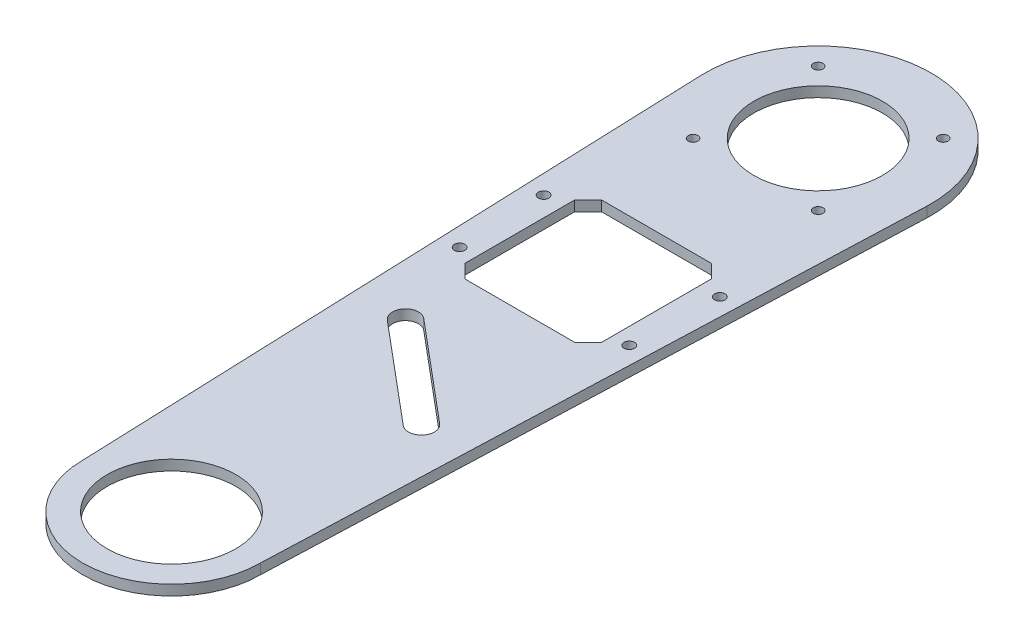
SolidWorks part; units mm, degrees
ref_plane "Front Plane" through (0, 0, 0) normal (0, 0, 1) x (1, 0, 0)
ref_plane "Top Plane" through (0, 0, 0) normal (0, 1, 0) x (1, 0, 0)
ref_plane "Right Plane" through (0, 0, 0) normal (1, 0, 0) x (0, 0, -1)
sketch "Sketch1" plane through (0, 0, 0) normal (0, 1, 0) x (1, 0, 0)
  line L0 (-27.5, -100) -> (-34.9753, 98.6841)
  line L1 (27.5, -100) -> (34.9753, 98.6841)
  arc A0 (-27.5, -100) -> (27.5, -100) centre (0, -100) ccw
  arc A2 (34.9753, 98.6841) -> (-34.9753, 98.6841) centre (0, 100) ccw
  dimension "D1" = 55
  dimension "D2" = 200
  dimension "D3" = 70
  dimension "D4" = 100
extrude "Boss-Extrude1" add sketch "Sketch1" along normal blind 3.175
sketch "Sketch2" plane through (0, 3.175, 0) normal (0, 1, 0) x (1, 0, 0)
  circle A0 centre (0, -100) radius 19.9
  circle A1 centre (0, 100) radius 19.9
  dimension "D1" = 39.8
  dimension "D2" = 200
  dimension "D3" = 100
extrude "Cut-Extrude1" cut sketch "Sketch2" against normal through all
sketch "Esquisse1" plane through (0, 3.175, 0) normal (0, 1, 0) x (1, 0, 0)
  circle A0 centre (0, 100) radius 27.35
  circle A2 centre (0, 100) radius 19.9 construction
  dimension "D1" = 54.7
sketch "Esquisse2" plane through (0, 3.175, 0) normal (0, 1, 0) x (1, 0, 0)
  line L0 (-19.3394, 80.6606) -> (19.3394, 80.6606) construction
  line L1 (19.3394, 80.6606) -> (19.3394, 119.3394) construction
  line L2 (19.3394, 119.3394) -> (-19.3394, 119.3394) construction
  line L3 (-19.3394, 119.3394) -> (-19.3394, 80.6606) construction
  circle A0 centre (19.3394, 80.6606) radius 1.5
  circle A2 centre (19.3394, 119.3394) radius 1.5
  circle A3 centre (-19.3394, 119.3394) radius 1.5
  circle A4 centre (-19.3394, 80.6606) radius 1.5
  circle A6 centre (0, 100) radius 27.35 construction
  point P2 (0, 80.6606)
  dimension "D1" = 3
extrude "Enlèv. mat.-Extru.1" cut sketch "Esquisse2" against normal through all
sketch "Sketch3" plane through (0, 3.175, 0) normal (0, 1, 0) x (1, 0, 0)
  circle A0 centre (0, 41.5664) radius 4.425
  dimension "D1" = 8.85
extrude "Cut-Extrude2" [suppressed] cut sketch "Sketch3" against normal through all
sketch "Sketch5" plane through (0, 3.175, 0) normal (0, 1, 0) x (1, 0, 0)
  line L0 (-21.15, 45.8281) -> (-16.9781, 50)
  line L1 (-16.9781, 50) -> (16.9781, 50)
  line L2 (16.9781, 50) -> (21.15, 45.8281)
  line L3 (21.15, 45.8281) -> (21.15, 11.8719)
  line L4 (21.15, 11.8719) -> (16.9781, 7.7)
  line L5 (16.9781, 7.7) -> (-16.9781, 7.7)
  line L6 (-16.9781, 7.7) -> (-21.15, 11.8719)
  line L7 (-21.15, 11.8719) -> (-21.15, 45.8281)
  circle A0 centre (-27.2565, 42.3405) radius 1.625
  circle A1 centre (-26.2414, 15.3595) radius 1.625
  circle A2 centre (26.2414, 15.3595) radius 1.625
  circle A3 centre (27.2565, 42.3405) radius 1.625
  dimension "D1" = 3.25
extrude "Cut-Extrude3" cut sketch "Sketch5" against normal through all
sketch "Sketch7" plane through (0, 3.175, 0) normal (0, 1, 0) x (1, 0, 0)
  line L6 (17.892, -34.9473) -> (-12.7497, -9.2358)
  line L9 (-17.892, -15.3642) -> (12.7497, -41.0757)
  arc A8 (-12.7497, -9.2358) -> (-17.892, -15.3642) centre (-15.3209, -12.3) ccw
  arc A9 (12.7497, -41.0757) -> (17.892, -34.9473) centre (15.3209, -38.0115) ccw
extrude "Cut-Extrude4" cut sketch "Sketch7" against normal through all
mirror "Mirror1" [suppressed] about plane through (0, 0, 0) normal (1, 0, 0)
